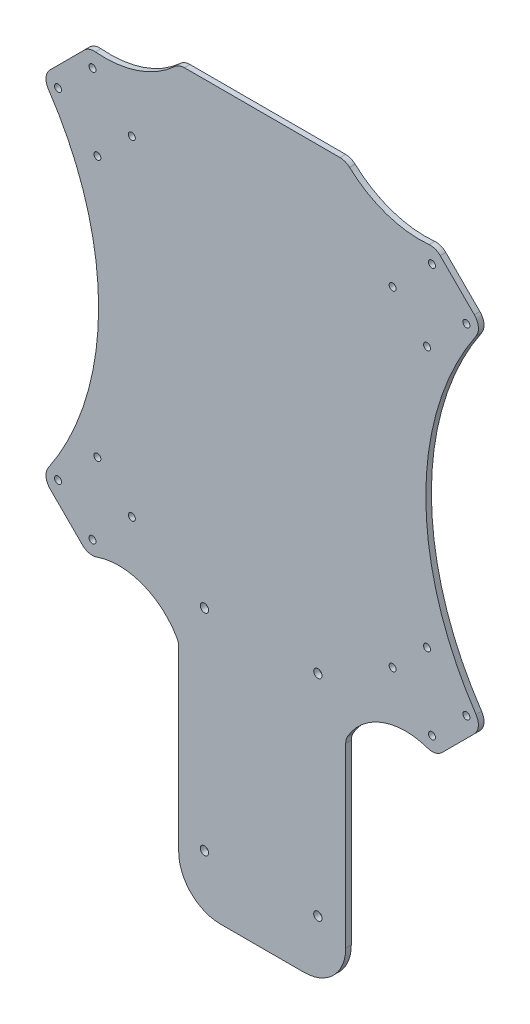
SolidWorks part; units mm, degrees
material "Hexcel AS4C (3000 Filaments)"
ref_plane "Front Plane" through (0, 0, 0) normal (0, 0, 1) x (1, 0, 0)
ref_plane "Top Plane" through (0, 0, 0) normal (0, 1, 0) x (1, 0, 0)
ref_plane "Right Plane" through (0, 0, 0) normal (1, 0, 0) x (0, 0, -1)
sketch "Sketch2" plane through (0, 0, 0) normal (0, 0, 1) x (1, 0, 0)
  line L0 (0, 0) -> (0, 50000) construction
  line L1 (0, 0) -> (35355.3391, 35355.3391) construction
  line L2 (0, 0) -> (35355.3391, -35355.3391) construction
  line L3 (-79.196, 62.2254) -> (-62.2254, 79.196)
  line L4 (0, 0) -> (-50000, 0) construction
  line L5 (-79.196, -62.2254) -> (-62.2254, -79.196)
  line L6 (30, 90) -> (-30, 90)
  line L7 (30, -90) -> (30, -155)
  line L8 (79.196, -62.2254) -> (62.2254, -79.196)
  line L9 (-30, -90) -> (-30, -155)
  line L10 (-15, -170) -> (15, -170)
  line L11 (79.196, 62.2254) -> (62.2254, 79.196)
  line L12 (-30, -90) -> (30, -170) construction
  line L13 (-30, -170) -> (30, -90) construction
  arc A0 (-79.196, 62.2254) -> (-79.196, -62.2254) centre (-163.8225, 0) cw
  arc A1 (-62.2254, 79.196) -> (-30, 90) centre (-56.6326, 115.976) ccw
  arc A2 (-62.2254, -79.196) -> (-30, -90) centre (-51.5147, -100.7107) cw
  arc A3 (15, -170) -> (30, -155) centre (15, -155) ccw
  arc A4 (-15, -170) -> (-30, -155) centre (-15, -155) cw
  arc A5 (62.2254, -79.196) -> (30, -90) centre (51.5147, -100.7107) ccw
  arc A6 (79.196, 62.2254) -> (79.196, -62.2254) centre (163.8225, 0) ccw
  arc A7 (62.2254, 79.196) -> (30, 90) centre (56.6326, 115.976) cw
  point P16 (-70.7107, 70.7107)
  point P24 (0, -130)
  point P32 (0, -170)
  point P45 (0, 90)
  dimension "D1" = 170
  dimension "D2" = 45
  dimension "D3" = 45
  dimension "D5" = 30
  dimension "D6" = 60
extrude "Boss-Extrude1" add sketch "Sketch2" along normal blind 2
sketch "Sketch3" plane through (0, 0, 2) normal (0, 0, 1) x (1, 0, 0)
  line L0 (-70.7107, 70.7107) -> (35284.6284, -35284.6284) construction
  line L1 (-79.196, 62.2254) -> (-62.2254, 79.196) construction
  line L2 (0, 90) -> (0, 50090) construction
  line L3 (30, 90) -> (-30, 90) construction
  line L4 (70.7107, 70.7107) -> (35426.0497, 35426.0497) construction
  line L5 (79.196, 62.2254) -> (62.2254, 79.196) construction
  line L6 (0, 0) -> (50000, 0) construction
  circle A0 centre (-73.3623, 60.988) radius 1.25
  circle A1 centre (-59.2202, 46.8458) radius 1.25
  circle A2 centre (-60.988, 73.3623) radius 1.25
  circle A3 centre (-46.8458, 59.2202) radius 1.25
  circle A4 centre (59.2202, 46.8458) radius 1.25
  circle A5 centre (73.3623, 60.988) radius 1.25
  circle A6 centre (60.988, 73.3623) radius 1.25
  circle A7 centre (46.8458, 59.2202) radius 1.25
  circle A8 centre (-59.2202, -46.8458) radius 1.25
  circle A9 centre (-46.8458, -59.2202) radius 1.25
  circle A10 centre (-60.988, -73.3623) radius 1.25
  circle A11 centre (-73.3623, -60.988) radius 1.25
  circle A12 centre (59.2202, -46.8458) radius 1.25
  circle A13 centre (73.3623, -60.988) radius 1.25
  circle A14 centre (60.988, -73.3623) radius 1.25
  circle A15 centre (46.8458, -59.2202) radius 1.25
  point P6 (-70.7107, 70.7107)
  point P17 (0, 90)
  point P30 (70.7107, 70.7107)
  dimension "D1" = 8.75
  dimension "D3" = 8.75
  dimension "D2" = 5
  dimension "D4" = 20
extrude "45 Degrees" cut sketch "Sketch3" against normal through all
sketch "Sketch4" plane through (0, 0, 2) normal (0, 0, 1) x (1, 0, 0)
  line L0 (30, -90) -> (30, -155) construction
  line L1 (-20.76, -74.5) -> (20, -74.5)
  line L2 (-20.76, -74.5) -> (-20.76, -150)
  line L3 (-20.76, -150) -> (20, -150)
  line L4 (20, -74.5) -> (20, -150)
  line L5 (-15, -170) -> (15, -170) construction
  circle A0 centre (-20.76, -150) radius 1.5
  circle A1 centre (20, -150) radius 1.5
  circle A2 centre (-20.76, -74.5) radius 1.5
  circle A3 centre (20, -74.5) radius 1.5
  dimension "D1" = 75.5
  dimension "D2" = 40.76
  dimension "D3" = 10
  dimension "D4" = 20
extrude "Cut-Extrude2" cut sketch "Sketch4" against normal through all contours A2 | A3 | A1 | A0
fillet "Fillet1" radius 5 1 edges at (-30, -90, 1)
fillet "Fillet2" radius 5 1 edges at (-62.2254, -79.196, 1)
fillet "Fillet3" radius 5 1 edges at (30, -90, 1)
fillet "Fillet4" radius 5 1 edges at (62.2254, -79.196, 1)
fillet "Fillet5" radius 5 1 edges at (79.196, -62.2254, 1)
fillet "Fillet6" radius 5 1 edges at (-79.196, -62.2254, 1)
fillet "Fillet7" radius 5 1 edges at (-79.196, 62.2254, 1)
fillet "Fillet8" radius 5 1 edges at (-62.2254, 79.196, 1)
fillet "Fillet9" radius 5 1 edges at (-30, 90, 1)
fillet "Fillet10" radius 5 1 edges at (30, 90, 1)
fillet "Fillet11" radius 5 1 edges at (62.2254, 79.196, 1)
fillet "Fillet12" radius 5 1 edges at (79.196, 62.2254, 1)
sketch "Sketch5" plane through (0, 0, 2) normal (0, 0, 1) x (1, 0, 0)
  line L0 (-62.1919, 74.1168) -> (-4609.0755, 2923.3707) construction
  line L1 (-59.8062, 63.4779) -> (-2909.0601, -4483.4057) construction
  line L2 (0, 0) -> (0, 50000) construction
  line L3 (27.9697, 90) -> (-27.9697, 90) construction
  line L4 (0, 0) -> (50000, 0) construction
  circle A0 centre (-60.988, 73.3623) radius 1.25
  circle A1 centre (-48.2774, 65.3974) radius 1.25
  circle A2 centre (-39.8591, 83.5394) radius 1.4408
  circle A3 centre (-50.368, 90.3098) radius 1.2775
  circle A4 centre (39.8591, 83.5394) radius 1.4408
  circle A5 centre (50.368, 90.3098) radius 1.2775
  circle A6 centre (48.2774, 65.3974) radius 1.25
  circle A7 centre (60.988, 73.3623) radius 1.25
  circle A8 centre (39.8591, -83.5394) radius 1.4408
  circle A9 centre (50.368, -90.3098) radius 1.2775
  circle A10 centre (60.988, -73.3623) radius 1.25
  circle A11 centre (48.2774, -65.3974) radius 1.25
  circle A12 centre (-39.8591, -83.5394) radius 1.4408
  circle A13 centre (-50.368, -90.3098) radius 1.2775
  circle A14 centre (-60.988, -73.3623) radius 1.25
  circle A15 centre (-48.2774, -65.3974) radius 1.25
  point P18 (0, 90)
  dimension "D2" = 8.75
  dimension "D1" = 6.25
  dimension "D3" = 20
  dimension "D4" = 20
  dimension "D5" = 6.25
  dimension "D6" = 6.25
extrude "35 Degrees" [suppressed] cut sketch "Sketch5" against normal through all
